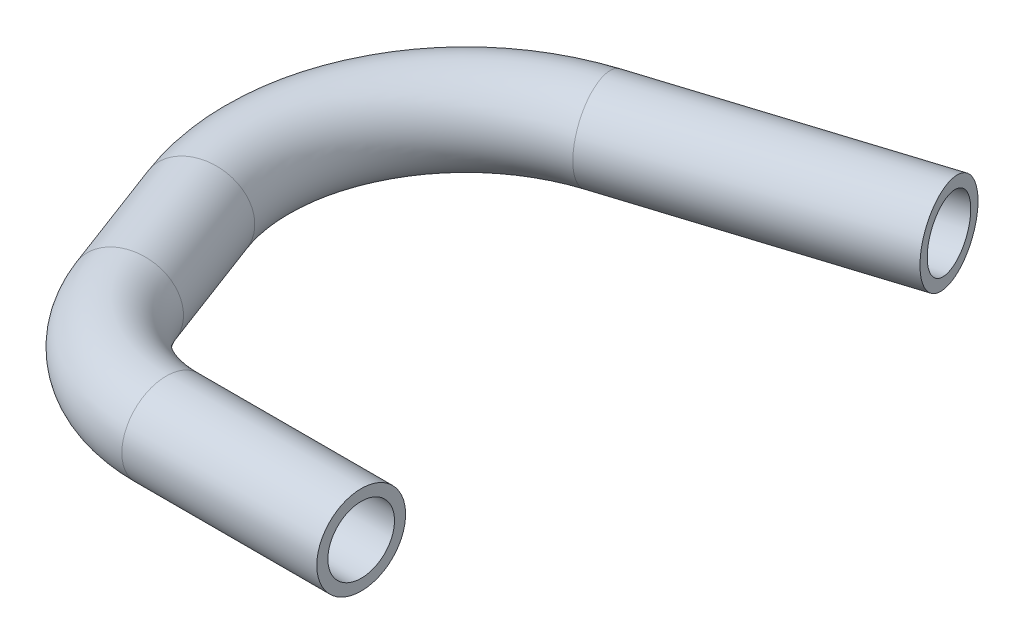
SolidWorks part; units mm, degrees
material "Silicon Rubber"
ref_plane "Plano frontal" through (0, 0, 0) normal (0, 0, 1) x (1, 0, 0)
ref_plane "Plano superior" through (0, 0, 0) normal (0, 1, 0) x (1, 0, 0)
ref_plane "Plano direito" through (0, 0, 0) normal (1, 0, 0) x (0, 0, -1)
sketch "Sketch1" plane through (0, 0, 0) normal (0, 1, 0) x (1, 0, 0)
  line L0 (-70.197, 0) -> (0, 0)
  line L1 (-116.9925, 32.3881) -> (-132.4963, 73.5821)
  line L2 (-84.8559, 171.5288) -> (10.197, 201.4988)
  line L3 (0, -110.8244) -> (0, 110.8244) construction
  line L4 (84.8559, 171.5288) -> (-10.197, 201.4988) construction
  line L5 (116.9925, 32.3881) -> (132.4963, 73.5821) construction
  line L6 (-116.9925, 32.3881) -> (-104.803, 0) construction
  line L7 (-104.803, 0) -> (-70.197, 0) construction
  arc A0 (-132.4963, 73.5821) -> (-84.8559, 171.5288) centre (-62.303, 100) cw
  arc A1 (-116.9925, 32.3881) -> (-70.197, 0) centre (-70.197, 50) ccw
  arc A2 (116.9925, 32.3881) -> (70.197, 0) centre (70.197, 50) cw construction
  arc A3 (132.4963, 73.5821) -> (84.8559, 171.5288) centre (62.303, 100) ccw construction
  point P17 (0, 0)
  dimension "D4" = 50
  dimension "D6" = 50
  dimension "D5" = 75
  dimension "D8" = 62.303
  dimension "D1" = 42.5
  dimension "D2" = 115
  dimension "D3" = 201.4988
  dimension "D7" = 70.197
  dimension "D9" = 145
sketch "Sketch2" plane through (0, 0, 0) normal (1, 0, 0) x (0, 0, -1)
  circle A0 centre (0, 0) radius 12
  circle A1 centre (0, 0) radius 16
  dimension "D1" = 24
  dimension "D2" = 32
sweep "Sweep1" add profiles "Sketch2" path "Sketch1"
